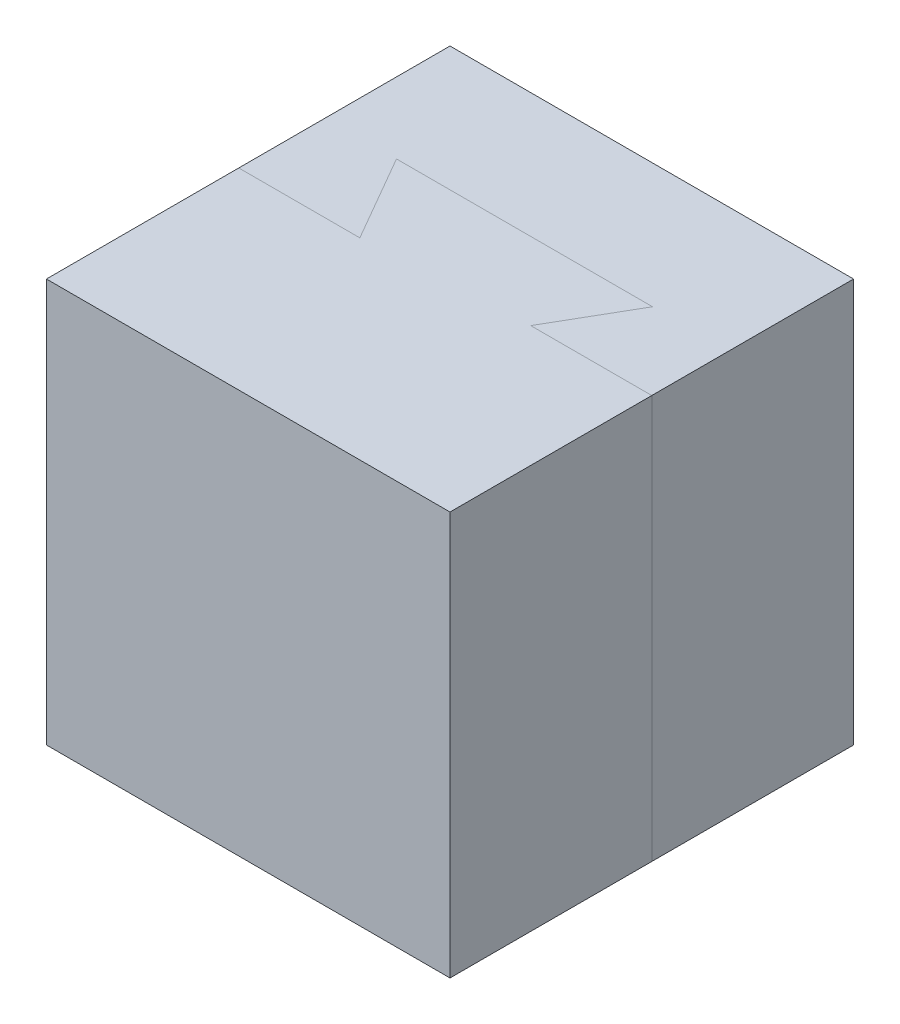
SolidWorks part; units mm, degrees
ref_plane "Front Plane" through (0, 0, 0) normal (0, 0, 1) x (1, 0, 0)
ref_plane "Top Plane" through (0, 0, 0) normal (0, 1, 0) x (1, 0, 0)
ref_plane "Right Plane" through (0, 0, 0) normal (1, 0, 0) x (0, 0, -1)
sketch "Sketch1" plane through (0, 0, 0) normal (0, 1, 0) x (1, 0, 0)
  line L1 (-5, 5) -> (5, 5)
  line L2 (-5, 5) -> (-5, -5)
  line L3 (-5, -5) -> (5, -5)
  line L4 (5, 5) -> (5, -5)
  line L5 (-5, 5) -> (5, -5) construction
  line L6 (-5, -5) -> (5, 5) construction
  point P0 (0, 0)
extrude "Boss-Extrude1" add sketch "Sketch1" along normal blind 10
sketch "Sketch2" plane through (0, 10, 0) normal (0, 1, 0) x (1, 0, 0)
  line L0 (-5, 5) -> (0, 5)
  line L1 (5, 5) -> (-5, 5) construction
sketch "Sketch3" plane through (0, 10, 0) normal (0, 1, 0) x (1, 0, 0)
  line L2 (-5, -0.2341) -> (-2, -0.2341)
  line L12 (-2, -0.2341) -> (-3.24, 1.9136)
  line L13 (-3.24, 1.9136) -> (3.1048, 1.9136)
  line L14 (3.1048, 1.9136) -> (2, 0)
  line L15 (2, 0) -> (5, 0)
  line L16 (5, -5) -> (5, 5) construction
  line L17 (-5, 5) -> (-5, -5) construction
  line L18 (-5, -0.2341) -> (-5, -5)
  line L19 (-5, -5) -> (5, -5)
  line L20 (5, -5) -> (5, 0)
  dimension "D1" = 3
  dimension "D2" = 3
  dimension "D3" = 60
  dimension "D4" = 60
split "Split2" trim tools "Sketch3" bodies to split 101 resulting bodies 104 105
